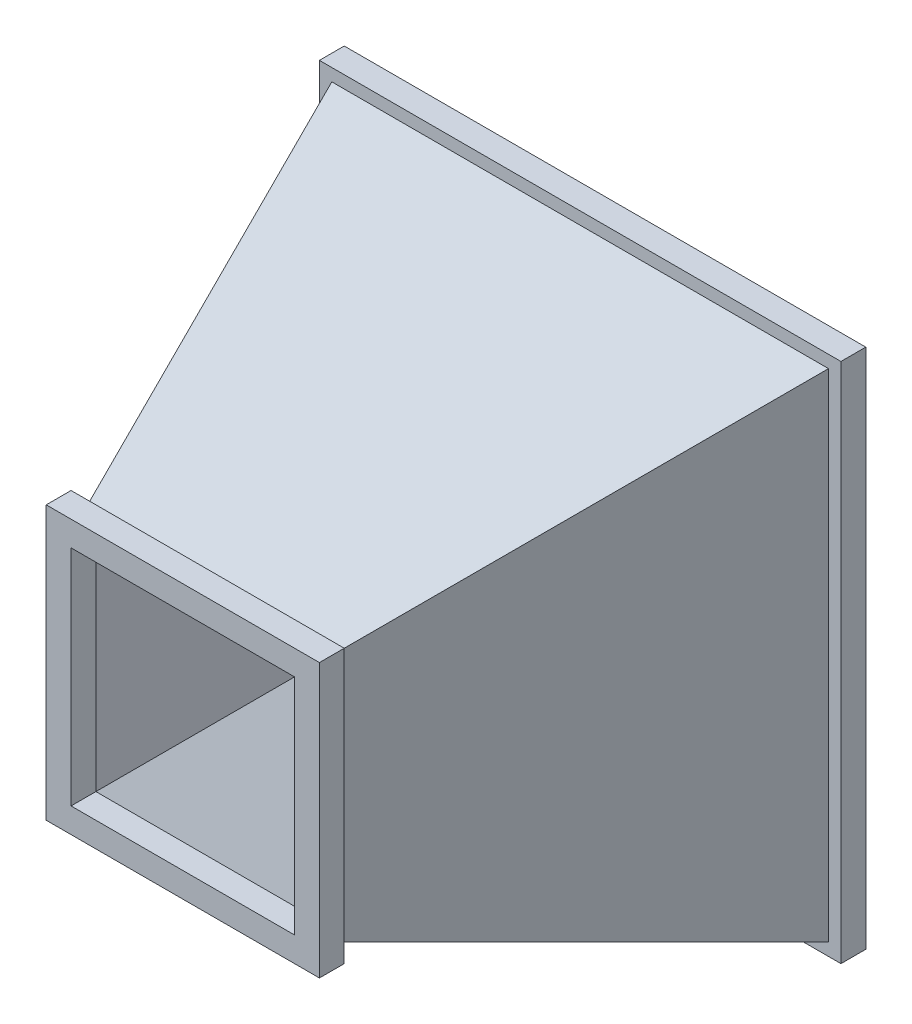
SolidWorks part; units mm, degrees
ref_plane "Front Plane" through (0, 0, 0) normal (0, 0, 1) x (1, 0, 0)
ref_plane "Top Plane" through (0, 0, 0) normal (0, 1, 0) x (1, 0, 0)
ref_plane "Right Plane" through (0, 0, 0) normal (1, 0, 0) x (0, 0, -1)
sketch "Sketch1" plane through (0, 0, 0) normal (0, 0, 1) x (1, 0, 0)
  line L1 (-254, -254) -> (254, -254)
  line L2 (-254, -254) -> (-254, 254)
  line L3 (-254, 254) -> (254, 254)
  line L4 (254, -254) -> (254, 254)
  line L5 (-254, -254) -> (254, 254) construction
  line L6 (-254, 254) -> (254, -254) construction
  point P0 (0, 0)
  dimension "D1" = 508
  dimension "D2" = 508
ref_plane "Plane1" through (0, 0, 381) normal (0, 0, 1) x (1, 0, 0)
sketch "Sketch2" plane through (0, 0, 381) normal (0, 0, 1) x (1, 0, 0)
  line L0 (-254, -254) -> (254, 254) construction
  line L1 (-127, -127) -> (127, -127)
  line L2 (-127, -127) -> (-127, 127)
  line L3 (-127, 127) -> (127, 127)
  line L4 (127, -127) -> (127, 127)
  line L5 (-127, -127) -> (127, 127) construction
  line L6 (-127, 127) -> (127, -127) construction
  point P0 (0, 0)
  dimension "D1" = 254
loft "Loft1" add profiles "Sketch2", "Sketch1"
sketch "Sketch3" plane through (0, 0, 381) normal (0, 0, 1) x (1, 0, 0)
  line L14 (114.3, -114.3) -> (114.3, 114.3)
  line L15 (-114.3, -114.3) -> (114.3, -114.3)
  line L16 (-114.3, 114.3) -> (-114.3, -114.3)
  line L17 (114.3, 114.3) -> (-114.3, 114.3)
  line L18 (114.3, -114.3) -> (114.3, 114.3)
  line L19 (-114.3, -114.3) -> (114.3, -114.3)
  line L20 (-114.3, 114.3) -> (-114.3, -114.3)
  line L21 (114.3, 114.3) -> (-114.3, 114.3)
  dimension "D1" = 12.7
sketch "Sketch4" plane through (0, 0, 0) normal (0, 0, -1) x (-1, 0, 0)
  line L14 (241.3, -241.3) -> (241.3, 241.3)
  line L15 (-241.3, -241.3) -> (241.3, -241.3)
  line L16 (-241.3, 241.3) -> (-241.3, -241.3)
  line L17 (241.3, 241.3) -> (-241.3, 241.3)
  line L18 (241.3, -241.3) -> (241.3, 241.3)
  line L19 (-241.3, -241.3) -> (241.3, -241.3)
  line L20 (-241.3, 241.3) -> (-241.3, -241.3)
  line L21 (241.3, 241.3) -> (-241.3, 241.3)
  dimension "D1" = 12.7
loft "Cut-Loft1" cut profiles "Sketch4", "Sketch3"
sketch "Sketch5" plane through (0, 0, 381) normal (0, 0, 1) x (1, 0, 0)
  line L1 (-114.3, -114.3) -> (114.3, -114.3)
  line L2 (-114.3, -114.3) -> (-114.3, 114.3)
  line L3 (-114.3, 114.3) -> (114.3, 114.3)
  line L4 (114.3, -114.3) -> (114.3, 114.3)
  line L5 (-114.3, -114.3) -> (114.3, 114.3) construction
  line L6 (-114.3, 114.3) -> (114.3, -114.3) construction
  line L20 (139.7, -139.7) -> (139.7, 139.7)
  line L21 (-139.7, -139.7) -> (139.7, -139.7)
  line L22 (-139.7, 139.7) -> (-139.7, -139.7)
  line L23 (139.7, 139.7) -> (-139.7, 139.7)
  line L24 (139.7, -139.7) -> (139.7, 139.7)
  line L25 (-139.7, -139.7) -> (139.7, -139.7)
  line L26 (-139.7, 139.7) -> (-139.7, -139.7)
  line L27 (139.7, 139.7) -> (-139.7, 139.7)
  point P0 (0, 0)
  dimension "D1" = 12.7
extrude "Boss-Extrude1" add sketch "Sketch5" along normal blind 25.4
sketch "Sketch6" plane through (0, 0, 0) normal (0, 0, -1) x (-1, 0, 0)
  line L1 (-241.3, -241.3) -> (241.3, -241.3)
  line L2 (-241.3, -241.3) -> (-241.3, 241.3)
  line L3 (-241.3, 241.3) -> (241.3, 241.3)
  line L4 (241.3, -241.3) -> (241.3, 241.3)
  line L5 (-241.3, -241.3) -> (241.3, 241.3) construction
  line L6 (-241.3, 241.3) -> (241.3, -241.3) construction
  line L20 (266.7, -266.7) -> (266.7, 266.7)
  line L21 (-266.7, -266.7) -> (266.7, -266.7)
  line L22 (-266.7, 266.7) -> (-266.7, -266.7)
  line L23 (266.7, 266.7) -> (-266.7, 266.7)
  line L24 (266.7, -266.7) -> (266.7, 266.7)
  line L25 (-266.7, -266.7) -> (266.7, -266.7)
  line L26 (-266.7, 266.7) -> (-266.7, -266.7)
  line L27 (266.7, 266.7) -> (-266.7, 266.7)
  point P0 (0, 0)
  dimension "D1" = 12.7
extrude "Boss-Extrude2" add sketch "Sketch6" along normal blind 25.4
